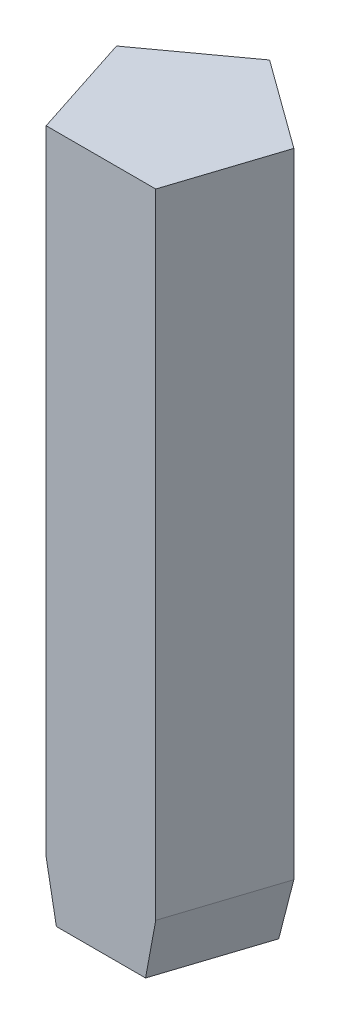
SolidWorks part; units mm, degrees
ref_plane "Front Plane" through (0, 0, 0) normal (0, 0, 1) x (1, 0, 0)
ref_plane "Top Plane" through (0, 0, 0) normal (0, 1, 0) x (1, 0, 0)
ref_plane "Right Plane" through (0, 0, 0) normal (1, 0, 0) x (0, 0, -1)
sketch "Sketch1" plane through (0, 0, 0) normal (0, 1, 0) x (1, 0, 0)
  line L1 (0, 6.7712) -> (-6.4398, 2.0924)
  line L2 (-6.4398, 2.0924) -> (-3.98, -5.478)
  line L3 (-3.98, -5.478) -> (3.98, -5.478)
  line L4 (3.98, -5.478) -> (6.4398, 2.0924)
  line L5 (6.4398, 2.0924) -> (0, 6.7712)
  circle A0 centre (0, 0) radius 5.478 construction
  dimension "D1" = 7.96
extrude "Boss-Extrude1" add sketch "Sketch1" along normal blind 50
chamfer "Chamfer1" distance 4 angle 10 5 edges at (-3.2199, 0, -4.4318) (-5.2099, 0, 1.6928) (0, 0, 5.478) (5.2099, 0, 1.6928) (3.2199, 0, -4.4318)
